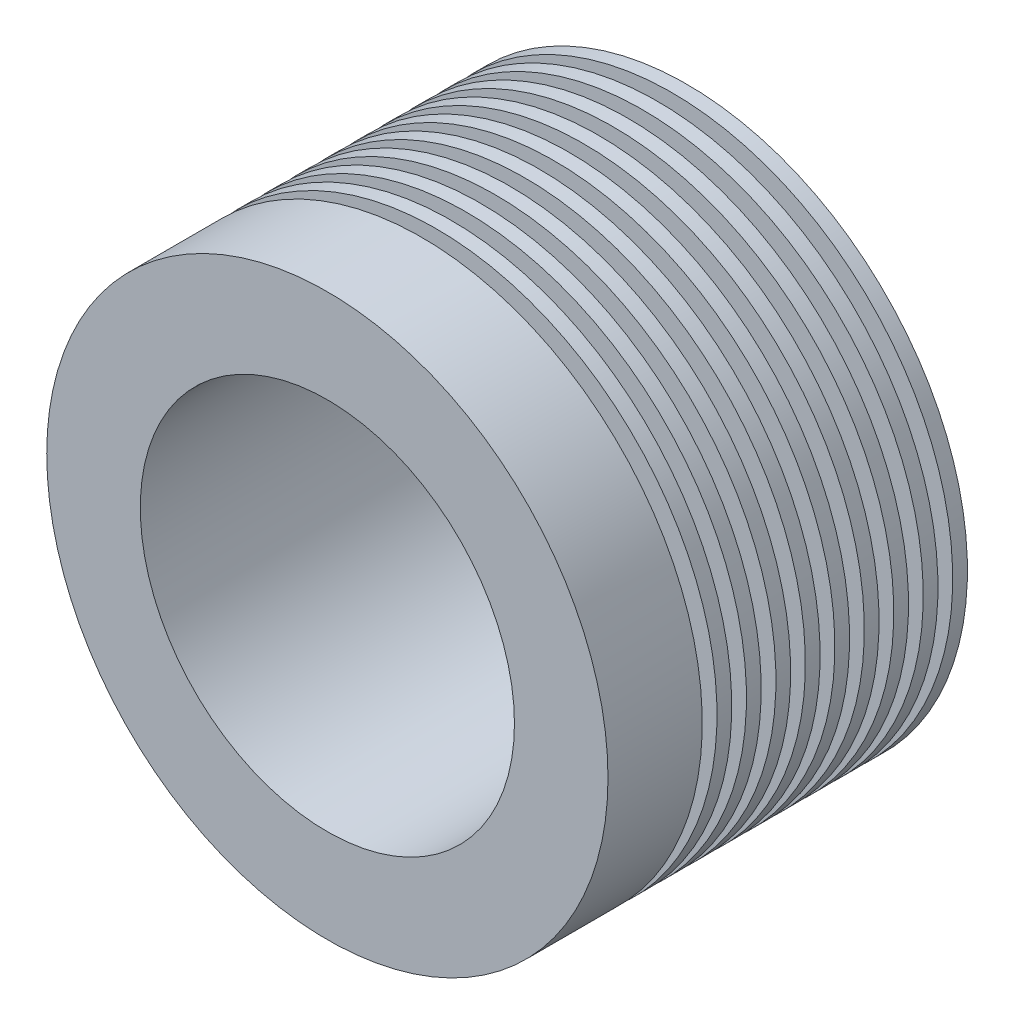
SolidWorks part; units mm, degrees
ref_plane "Plan de face" through (0, 0, 0) normal (0, 0, 1) x (1, 0, 0)
ref_plane "Plan de dessus" through (0, 0, 0) normal (0, 1, 0) x (1, 0, 0)
ref_plane "Plan de droite" through (0, 0, 0) normal (1, 0, 0) x (0, 0, -1)
sketch "Esquisse1" plane through (0, 0, 0) normal (0, 0, 1) x (1, 0, 0)
  circle A0 centre (0, 0) radius 38.1
extrude "Boss.-Extru.1" add sketch "Esquisse1" along normal blind 50.8
sketch "Esquisse2" plane through (0, 0, 0) normal (0, 0, -1) x (-1, 0, 0)
  circle A0 centre (0, 0) radius 31.75
  point P3 (-148.2996, 19.0013)
extrude "Enlèv. mat.-Extru.3" cut sketch "Esquisse2" against normal blind 2 flip side to cut
pattern_linear "Répétition linéaire1" count 10 spacing 4 along (0, 0, 1) of "Enlèv. mat.-Extru.3"
sketch "Esquisse5" plane through (0, 0, 50.8) normal (0, 0, 1) x (1, 0, 0)
  circle A0 centre (0, 0) radius 25.4
extrude "Enlèv. mat.-Extru.5" cut sketch "Esquisse5" against normal blind 38.1
